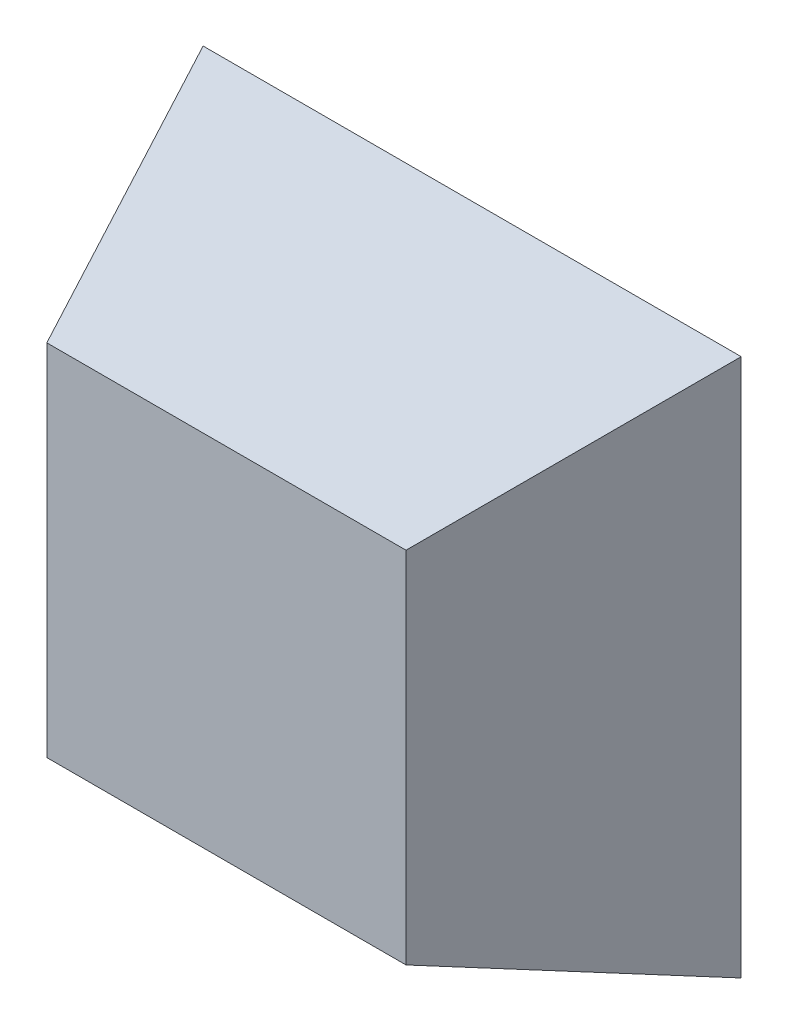
SolidWorks part; units mm, degrees
ref_plane "Face" through (0, 0, 0) normal (0, 0, 1) x (1, 0, 0)
ref_plane "Dessus" through (0, 0, 0) normal (0, 1, 0) x (1, 0, 0)
ref_plane "Droite" through (0, 0, 0) normal (1, 0, 0) x (0, 0, -1)
sketch "Esquisse1" plane through (0, 0, 0) normal (0, 0, 1) x (1, 0, 0)
  line L8 (91.85, -92.15) -> (79.15, -92.15)
  line L9 (91.85, -104.85) -> (91.85, -92.15)
  line L10 (79.15, -104.85) -> (91.85, -104.85)
  line L11 (79.15, -92.15) -> (79.15, -104.85)
extrude "Base-Extrusion" add sketch "Esquisse1" along normal blind 5.8 draft 20
